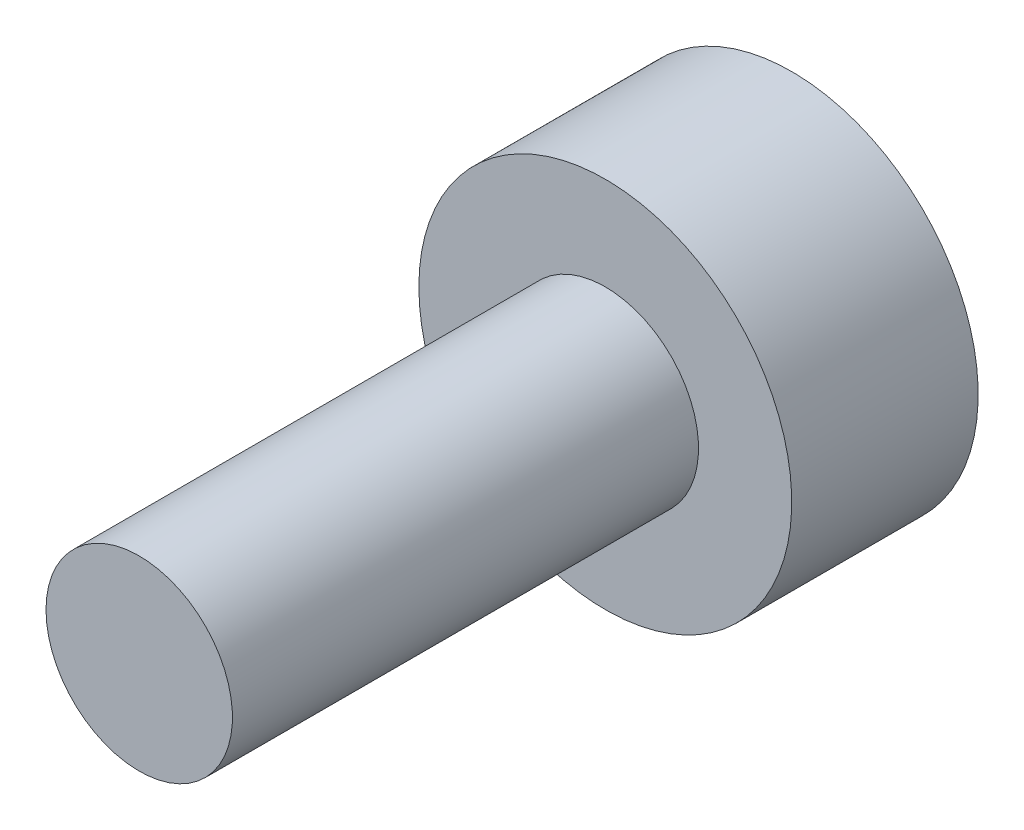
SolidWorks part; units mm, degrees
ref_plane "Płaszczyzna przednia" through (0, 0, 0) normal (0, 0, 1) x (1, 0, 0)
ref_plane "Płaszczyzna górna" through (0, 0, 0) normal (0, 1, 0) x (1, 0, 0)
ref_plane "Płaszczyzna prawa" through (0, 0, 0) normal (1, 0, 0) x (0, 0, -1)
sketch "Sketch1" plane through (0, 0, 0) normal (0, 1, 0) x (1, 0, 0)
  line L0 (0, 0) -> (1, 0)
  line L1 (1, 0) -> (1, 5)
  line L2 (1, 5) -> (2, 5)
  line L3 (2, 5) -> (2, 7)
  line L4 (2, 7) -> (0, 7)
  line L5 (0, 7) -> (0, 0)
  dimension "D1" = 2
  dimension "D2" = 1
  dimension "D3" = 2
  dimension "D4" = 5
revolve "Revolve1" add sketch "Sketch1" angle 360 about L5
sketch "Sketch2" plane through (0, 0, -7) normal (0, 0, -1) x (-1, 0, 0)
  line L1 (0.433, 0.75) -> (-0.433, 0.75)
  line L2 (-0.433, 0.75) -> (-0.866, 0)
  line L3 (-0.866, 0) -> (-0.433, -0.75)
  line L4 (-0.433, -0.75) -> (0.433, -0.75)
  line L5 (0.433, -0.75) -> (0.866, 0)
  line L6 (0.866, 0) -> (0.433, 0.75)
  circle A0 centre (0, 0) radius 0.75 construction
  dimension "D1" = 1.5
extrude "Cut-Extrude1" cut sketch "Sketch2" against normal blind 1.2
